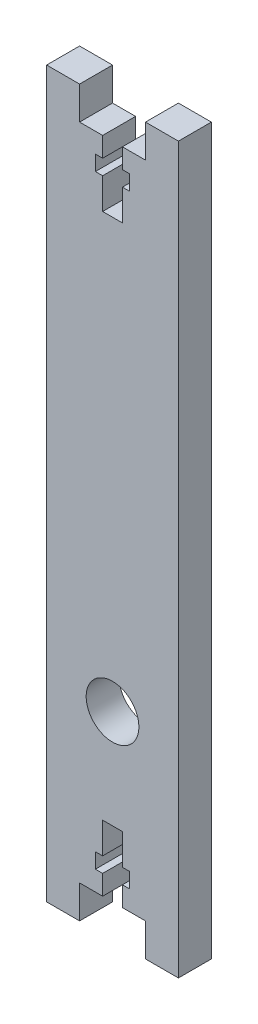
SolidWorks part; units mm, degrees
ref_plane "Front Plane" through (0, 0, 0) normal (0, 0, 1) x (1, 0, 0)
ref_plane "Top Plane" through (0, 0, 0) normal (0, 1, 0) x (1, 0, 0)
ref_plane "Right Plane" through (0, 0, 0) normal (1, 0, 0) x (0, 0, -1)
sketch "Sketch1" plane through (0, 0, 0) normal (0, 0, 1) x (1, 0, 0)
  line L0 (-24.2111, 40) -> (17.8355, 40) construction
  line L1 (-10, 80) -> (-10, -20)
  line L2 (10, 80) -> (10, -20)
  line L3 (0, 80) -> (0, 68.7792) construction
  line L4 (-1.5, 80) -> (-5, 80)
  line L5 (-5, 85) -> (-10, 85)
  line L6 (-10, 85) -> (-10, 80)
  line L7 (-5, 85) -> (-5, 80)
  line L8 (1.5, 80) -> (5, 80)
  line L9 (5, 80) -> (5, 85)
  line L10 (5, 85) -> (10, 85)
  line L11 (10, 85) -> (10, 80)
  line L12 (0, -20) -> (0, 11.2208) construction
  line L13 (-1.5, -20) -> (-5, -20)
  line L14 (-5, -25) -> (-10, -25)
  line L15 (-10, -25) -> (-10, -20)
  line L16 (-5, -25) -> (-5, -20)
  line L17 (1.5, -20) -> (5, -20)
  line L18 (5, -20) -> (5, -25)
  line L19 (5, -25) -> (10, -25)
  line L20 (10, -25) -> (10, -20)
  line L21 (-1.5, -20) -> (1.5, -20) construction
  line L22 (1.5, -20) -> (1.5, -17)
  line L23 (1.5, -14.7) -> (2.6, -14.7)
  line L24 (-2.6, -17) -> (-2.6, -14.7)
  line L25 (2.6, -17) -> (1.5, -17)
  line L26 (1.5, -14.7) -> (1.5, -10)
  line L27 (1.5, -10) -> (-1.5, -10)
  line L28 (-1.5, -10) -> (-1.5, -14.7)
  line L29 (-1.5, -17) -> (-2.6, -17)
  line L30 (2.6, -14.7) -> (2.6, -17)
  line L31 (-2.6, -14.7) -> (-1.5, -14.7)
  line L32 (-1.5, -17) -> (-1.5, -20)
  line L33 (0, -10) -> (0, -20) construction
  line L34 (-1.5, 80) -> (1.5, 80) construction
  line L35 (1.5, 80) -> (1.5, 77)
  line L36 (1.5, 74.7) -> (2.6, 74.7)
  line L37 (-2.6, 77) -> (-2.6, 74.7)
  line L38 (2.6, 77) -> (1.5, 77)
  line L39 (1.5, 74.7) -> (1.5, 70)
  line L40 (1.5, 70) -> (-1.5, 70)
  line L41 (-1.5, 70) -> (-1.5, 74.7)
  line L42 (-1.5, 77) -> (-2.6, 77)
  line L43 (2.6, 74.7) -> (2.6, 77)
  line L44 (-2.6, 74.7) -> (-1.5, 74.7)
  line L45 (-1.5, 77) -> (-1.5, 80)
  line L46 (0, 70) -> (0, 80) construction
  line L47 (0, 40) -> (0, 18.178) construction
  circle A0 centre (0, 5) radius 4
  dimension "D18" = 8
  dimension "D1" = 100
  dimension "D2" = 10
  dimension "D3" = 5
  dimension "D4" = 5
  dimension "D5" = 10
  dimension "D6" = 5
  dimension "D7" = 5
  dimension "D8" = 5.2
  dimension "D9" = 3
  dimension "D10" = 2.3
  dimension "D11" = 3
  dimension "D12" = 10
  dimension "D13" = 5.2
  dimension "D14" = 3
  dimension "D15" = 2.3
  dimension "D16" = 3
  dimension "D17" = 10
  dimension "D19" = 75
extrude "Boss-Extrude1" add sketch "Sketch1" along normal blind 5
